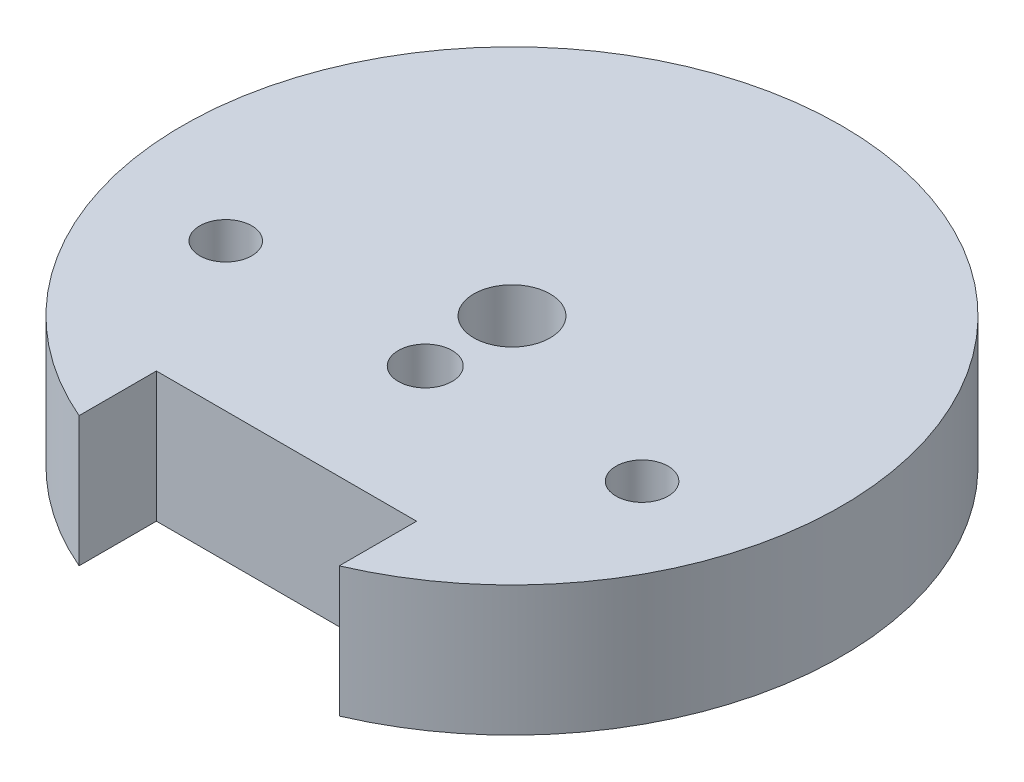
SolidWorks part; units mm, degrees
ref_plane "Front Plane" through (0, 0, 0) normal (0, 0, 1) x (1, 0, 0)
ref_plane "Top Plane" through (0, 0, 0) normal (0, 1, 0) x (1, 0, 0)
ref_plane "Right Plane" through (0, 0, 0) normal (1, 0, 0) x (0, 0, -1)
sketch "Sketch1" plane through (0, 0, 0) normal (0, 1, 0) x (1, 0, 0)
  line L0 (0, 0) -> (0, -49.53) construction
  line L1 (19.05, -33.02) -> (-19.05, -33.02)
  line L2 (-19.05, -33.02) -> (-19.05, -45.72)
  line L3 (19.05, -33.02) -> (19.05, -45.72)
  line L4 (-19.05, -45.72) -> (-19.05, -61.7062)
  line L5 (-19.05, -61.7062) -> (19.05, -61.7062)
  line L6 (19.05, -61.7062) -> (19.05, -45.72)
  line L7 (0, 0) -> (-49.53, 0) construction
  circle A0 centre (0, 0) radius 49.53
  circle A1 centre (0, 0) radius 5.588
  circle A2 centre (-30.48, -11.43) radius 3.81
  circle A3 centre (30.48, -11.43) radius 3.81
  circle A4 centre (0, -12.7) radius 3.937
  point P9 (0, -33.02)
  dimension "D1" = 99.06
  dimension "D2" = 11.176
  dimension "D5" = 7.62
  dimension "D8" = 7.874
  dimension "D3" = 38.1
  dimension "D4" = 12.7
  dimension "D6" = 11.43
  dimension "D7" = 30.48
  dimension "D9" = 12.7
extrude "Boss-Extrude1" add sketch "Sketch1" along normal blind 19.05 contours L3 A0 L2 L1 A1 A2 A3
sketch "Sketch2" plane through (0, 0, 0) normal (0, 1, 0) x (1, 0, 0)
  line L1 (-87.7545, -62.3638) -> (87.7545, -62.3638)
  line L2 (-87.7545, -62.3638) -> (-87.7545, 62.3638)
  line L3 (-87.7545, 62.3638) -> (87.7545, 62.3638)
  line L4 (87.7545, -62.3638) -> (87.7545, 62.3638)
  line L5 (-87.7545, -62.3638) -> (87.7545, 62.3638) construction
  line L6 (-87.7545, 62.3638) -> (87.7545, -62.3638) construction
  circle A0 centre (0, 0) radius 48.26
  dimension "D1" = 96.52
extrude "Tolerance Adjust" cut sketch "Sketch2" along normal blind 63.5
